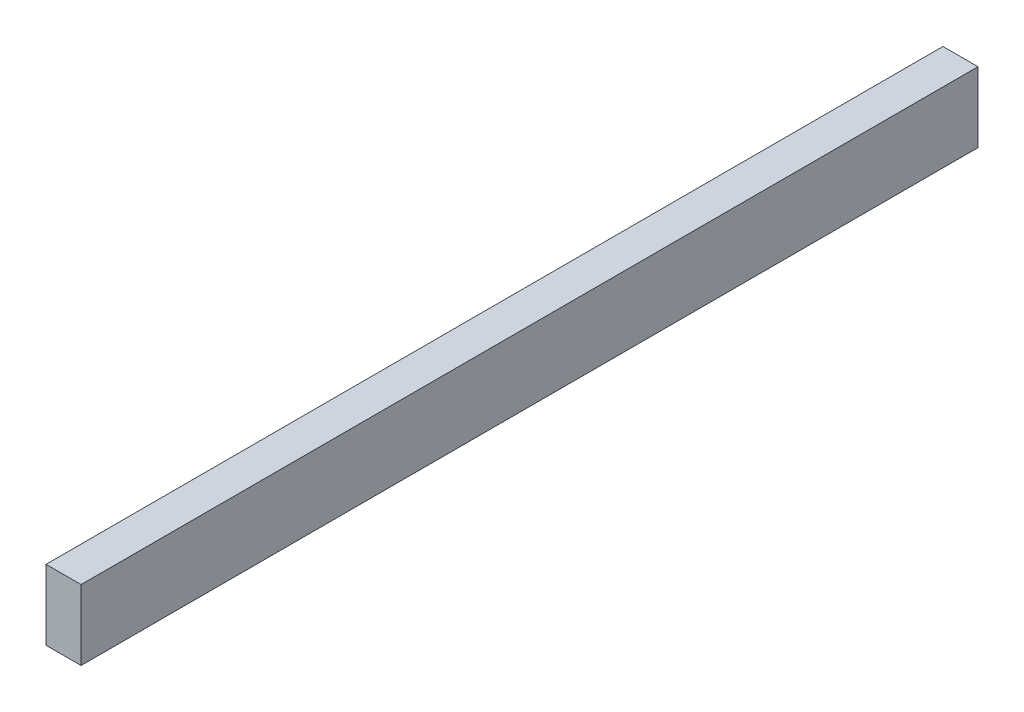
SolidWorks part; units mm, degrees
ref_plane "Front Plane" through (0, 0, 0) normal (0, 0, 1) x (1, 0, 0)
ref_plane "Top Plane" through (0, 0, 0) normal (0, 1, 0) x (1, 0, 0)
ref_plane "Right Plane" through (0, 0, 0) normal (1, 0, 0) x (0, 0, -1)
sketch "Sketch1" plane through (0, 0, 0) normal (0, 0, 1) x (1, 0, 0)
  line L1 (0, 0) -> (50.8, 0)
  line L2 (0, 0) -> (0, 101.6)
  line L3 (0, 101.6) -> (50.8, 101.6)
  line L4 (50.8, 0) -> (50.8, 101.6)
  dimension "D1" = 50.8
  dimension "D2" = 101.6
extrude "Boss-Extrude1" add sketch "Sketch1" along normal blind 1300
